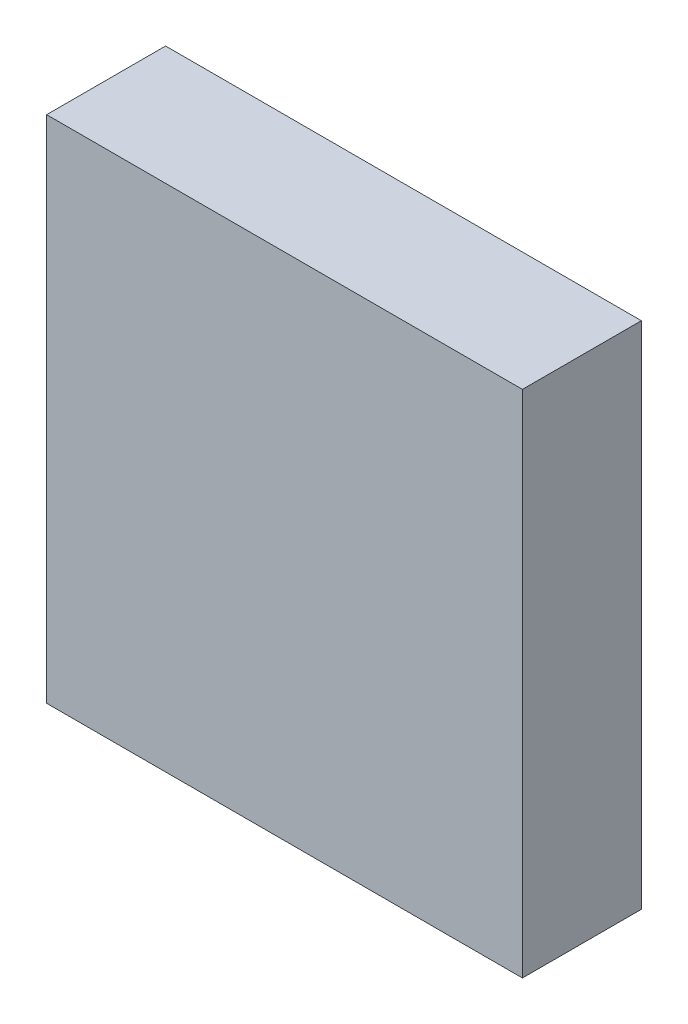
SolidWorks part; units mm, degrees
ref_plane "Plan de face" through (0, 0, 0) normal (0, 0, 1) x (1, 0, 0)
ref_plane "Plan de dessus" through (0, 0, 0) normal (0, 1, 0) x (1, 0, 0)
ref_plane "Plan de droite" through (0, 0, 0) normal (1, 0, 0) x (0, 0, -1)
sketch "Esquisse1" plane through (0, 0, 0) normal (0, 0, 1) x (1, 0, 0)
  line L1 (-70, -75) -> (70, -75)
  line L2 (-70, -75) -> (-70, 75)
  line L3 (-70, 75) -> (70, 75)
  line L4 (70, -75) -> (70, 75)
extrude "Boitier_alimentation_5V" add sketch "Esquisse1" along normal blind 35
sketch "Esquisse2" plane through (0, 0, 0) normal (0, 0, 1) x (1, 0, 0)
  line L1 (-45, -81) -> (45, -81)
  line L2 (-45, -81) -> (-45, -75)
  line L3 (-45, -75) -> (45, -75)
  line L4 (45, -81) -> (45, -75)
extrude "Bornier_puissance" add sketch "Esquisse2" along normal blind 16 from offset 4
